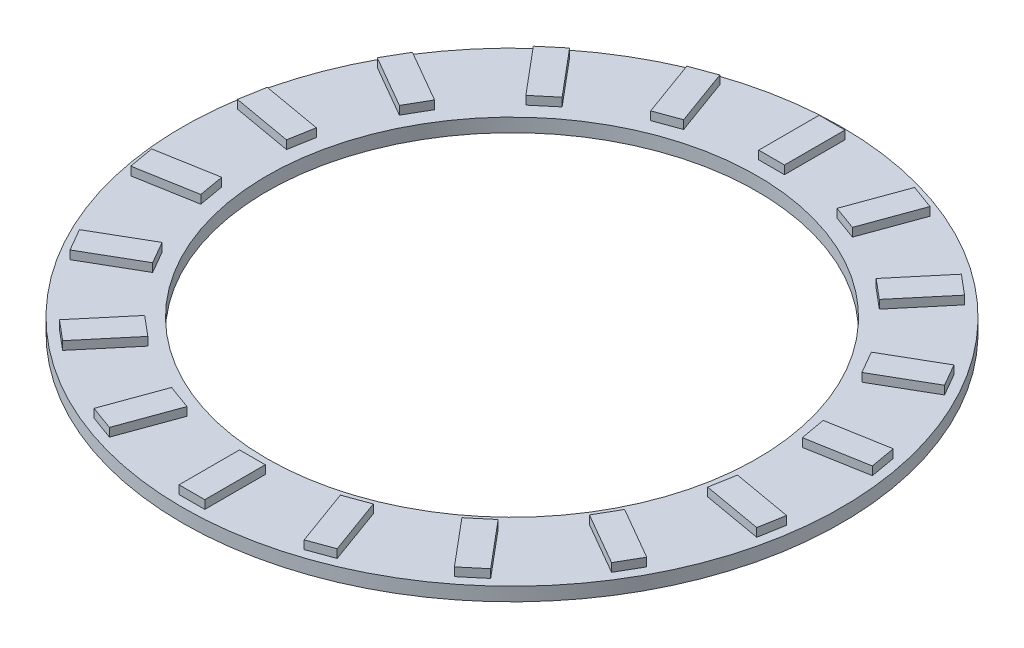
SolidWorks part; units mm, degrees
ref_plane "前视基准面" through (0, 0, 0) normal (0, 0, 1) x (1, 0, 0)
ref_plane "上视基准面" through (0, 0, 0) normal (0, 1, 0) x (1, 0, 0)
ref_plane "右视基准面" through (0, 0, 0) normal (1, 0, 0) x (0, 0, -1)
sketch "草图1" plane through (0, 0, 0) normal (0, 1, 0) x (1, 0, 0)
  circle A0 centre (0, 0) radius 29
  circle A1 centre (0, 0) radius 39
  dimension "D1" = 58
  dimension "D2" = 78
extrude "凸台-拉伸1" add sketch "草图1" along normal blind 1.6
sketch "草图2" plane through (0, 1.6, 0) normal (0, 1, 0) x (1, 0, 0)
  line L0 (0, 0) -> (0, 41.1535) construction
  line L2 (-1.5228, 37.8795) -> (1.5228, 37.8795)
  line L3 (-1.5228, 37.8795) -> (-1.5228, 30.7224)
  line L4 (-1.5228, 30.7224) -> (1.5228, 30.7224)
  line L5 (1.5228, 37.8795) -> (1.5228, 30.7224)
  line L6 (-1.5228, 37.8795) -> (1.5228, 30.7224) construction
  line L7 (-1.5228, 30.7224) -> (1.5228, 37.8795) construction
  point P2 (0, 34.301)
extrude "凸台-拉伸2" add sketch "草图2" along normal blind 1
pattern_circular "阵列(圆周)1" count 18 over 360 about axis through (0, 0, 0) along (0, 1, 0) of "凸台-拉伸2"
